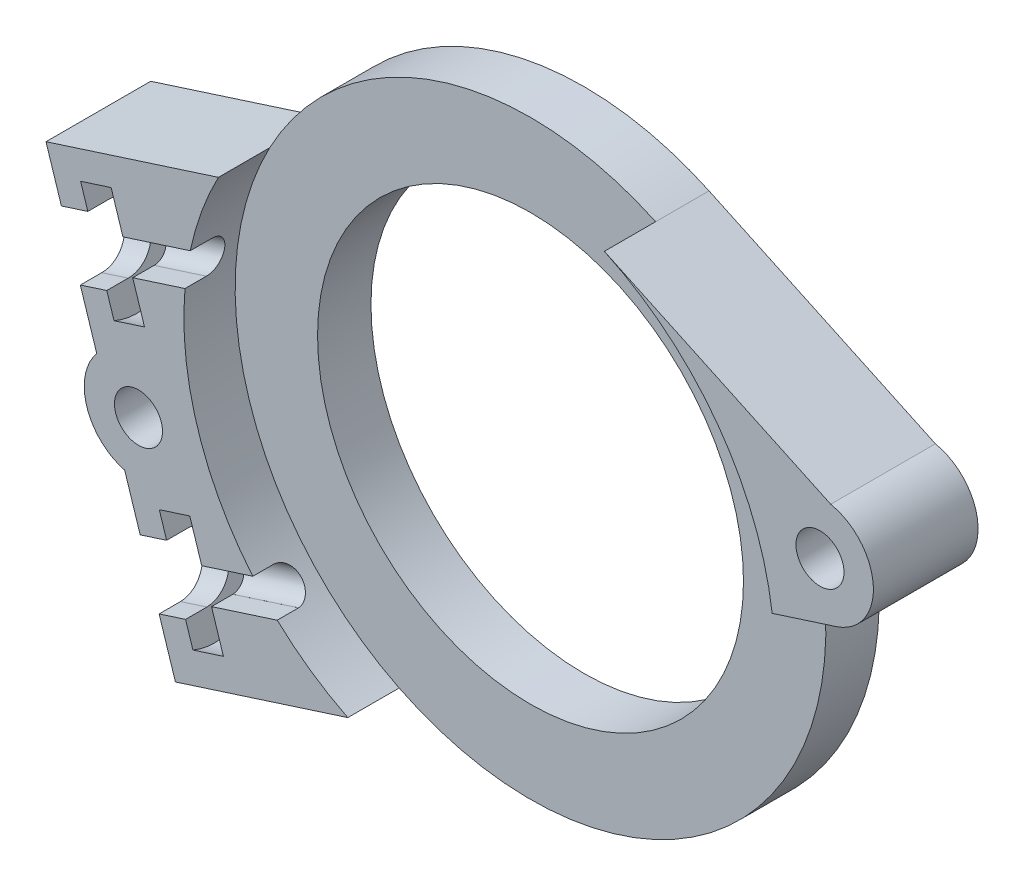
SolidWorks part; units mm, degrees
ref_plane "Alzado" through (0, 0, 0) normal (0, 0, 1) x (1, 0, 0)
ref_plane "Planta" through (0, 0, 0) normal (0, 1, 0) x (1, 0, 0)
ref_plane "Vista lateral" through (0, 0, 0) normal (1, 0, 0) x (0, 0, -1)
sketch "Croquis1" plane through (0, 0, 0) normal (0, 0, 1) x (1, 0, 0)
  circle A1 centre (0, 0) radius 27.65
extrude "Saliente-Extruir1" add sketch "Croquis1" along normal blind 5
sketch "Croquis2" plane through (0, 0, 0) normal (0, 0, -1) x (-1, 0, 0)
  line L0 (-33.4252, 5.4777) -> (-27.4211, 3.5505) construction
  line L1 (-11.7136, 25.0462) -> (-32.9036, 15.1362) construction
  line L2 (-33.4252, 5.4777) -> (-27.4211, 3.5505)
  line L3 (-11.7136, 25.0462) -> (-32.9036, 15.1362)
  line L6 (40.5555, 7.7982) -> (24.4143, 12.9793) construction
  line L7 (38.8632, 2.5261) -> (40.5555, 7.7982) construction
  line L8 (12.2993, -24.7639) -> (28.4405, -29.9449) construction
  line L9 (28.4405, -29.9449) -> (30.1924, -24.4871) construction
  line L10 (40.5555, 7.7982) -> (24.4143, 12.9793)
  line L11 (38.8632, 2.5261) -> (40.5555, 7.7982)
  line L12 (12.2993, -24.7639) -> (28.4405, -29.9449)
  line L13 (28.4405, -29.9449) -> (30.1924, -24.4871)
  line L14 (38.8632, 2.5261) -> (35.8059, -6.9986)
  line L15 (33.1901, -15.1481) -> (30.1924, -24.4871)
  line L16 (30.1924, -24.4871) -> (30.5309, -24.1624)
  arc A0 (-32.9036, 15.1362) -> (-33.4252, 5.4777) centre (-31.8971, 10.2385) ccw construction
  circle A1 centre (-31.8971, 10.2385) radius 2.25 construction
  arc A2 (-32.9036, 15.1362) -> (-33.4252, 5.4777) centre (-31.8971, 10.2385) ccw
  circle A3 centre (-31.8971, 10.2385) radius 2.25
  arc A6 (33.1901, -15.1481) -> (35.8059, -6.9986) centre (31.8971, -10.2385) ccw construction
  arc A7 (33.1901, -15.1481) -> (35.8059, -6.9986) centre (31.8971, -10.2385) ccw
  circle A8 centre (31.8971, -10.2385) radius 2.25 construction
  circle A9 centre (31.8971, -10.2385) radius 2.25
  circle A10 centre (0, 0) radius 27.65 construction
  arc A11 (-27.4211, 3.5505) -> (12.2993, -24.7639) centre (0, 0) ccw
  arc A12 (24.4143, 12.9793) -> (-11.7136, 25.0462) centre (0, 0) ccw
extrude "Saliente-Extruir2" add sketch "Croquis2" against normal up to vertex (9.8 mm away)
sketch "Croquis8" plane through (0, 0, 0) normal (0, 0, -1) x (-1, 0, 0)
  circle A0 centre (0, 0) radius 19.9363
extrude "Cortar-Extruir8" cut sketch "Croquis8" against normal through all
chamfer "Chaflán1" distance 1 angle 45 2 edges at (29.6471, 10.2385, 0) (-34.1471, -10.2385, 0)
sketch "Croquis14" plane through (-34.498, -11.0734, 0) normal (0.9522, 0.3056, 0) x (0, 0, -1)
  circle A0 centre (-7.7786, 12.2034) radius 2.9 construction
  circle A1 centre (-7.7786, 12.2034) radius 2.9
sketch "Croquis15" plane through (-32.0224, -10.2787, 0) normal (-0.9522, -0.3056, 0) x (0, 0, 1)
  circle A0 centre (7.7786, 12.2034) radius 5.5 construction
  circle A1 centre (7.7786, 12.2034) radius 5.5
sketch "Croquis16" plane through (-29.5468, -9.4841, 0) normal (0.9522, 0.3056, 0) x (0, 0, -1)
  circle A0 centre (-7.7786, 12.2034) radius 1.5 construction
  circle A1 centre (-7.7786, 12.2034) radius 1.5
sketch "Croquis18" plane through (-34.498, -11.0734, 0) normal (0.9522, 0.3056, 0) x (0, 0, -1)
  circle A0 centre (-7.8672, -11.9258) radius 2.9 construction
  circle A1 centre (-7.8672, -11.9258) radius 2.9
sketch "Croquis19" plane through (-32.0224, -10.2787, 0) normal (-0.9522, -0.3056, 0) x (0, 0, 1)
  circle A0 centre (7.8672, -11.9258) radius 5.5 construction
  circle A1 centre (7.8672, -11.9258) radius 5.5
sketch "Croquis20" plane through (-29.5468, -9.4841, 0) normal (0.9522, 0.3056, 0) x (0, 0, -1)
  circle A0 centre (-7.8672, -11.9258) radius 1.5 construction
  circle A1 centre (-7.8672, -11.9258) radius 1.5
extrude "Cortar-Extruir15" cut sketch "Croquis14" along normal blind 3
extrude "Cortar-Extruir16" cut sketch "Croquis15" against normal blind 3
extrude "Cortar-Extruir17" cut sketch "Croquis16" along normal blind 25
extrude "Cortar-Extruir18" cut sketch "Croquis18" along normal blind 3
extrude "Cortar-Extruir19" cut sketch "Croquis19" against normal blind 3
extrude "Cortar-Extruir20" cut sketch "Croquis20" along normal blind 22
sketch "Croquis21" plane through (0, 0, 9.8) normal (0, 0, 1) x (1, 0, 0)
  line L0 (-25.9795, -19.2888) -> (-25.0627, -22.1452) construction
  line L1 (-25.9795, -19.2888) -> (-25.0627, -22.1452)
  line L2 (-33.3541, 3.6859) -> (-32.4372, 0.8294) construction
  line L3 (-33.3541, 3.6859) -> (-32.4372, 0.8294)
  line L4 (-21.1973, -17.7538) -> (-25.9795, -19.2888)
  line L5 (-18.9118, -20.1709) -> (-25.0627, -22.1452)
  line L6 (-27.5457, 2.3996) -> (-32.4372, 0.8294)
  line L7 (-27.0544, 5.708) -> (-33.3541, 3.6859)
  line L8 (-39.114, 3.3074) -> (-37.3414, -2.2151) construction
  line L9 (-39.114, 3.3074) -> (-37.3414, -2.2151)
  line L10 (-31.7395, -19.6673) -> (-29.9668, -25.1898) construction
  line L11 (-31.7395, -19.6673) -> (-29.9668, -25.1898)
  line L12 (-34.8658, -1.4204) -> (-36.6384, 4.102) construction
  line L13 (-34.8658, -1.4204) -> (-36.6384, 4.102)
  line L14 (-27.4912, -24.3951) -> (-29.2639, -18.8726) construction
  line L15 (-27.4912, -24.3951) -> (-29.2639, -18.8726)
  line L16 (-39.114, 3.3074) -> (-36.6384, 4.102)
  line L17 (-37.3414, -2.2151) -> (-34.8658, -1.4204)
  line L18 (-31.7395, -19.6673) -> (-29.2639, -18.8726)
  line L19 (-27.4912, -24.3951) -> (-29.9668, -25.1898)
  arc A0 (-21.1973, -17.7538) -> (-18.9118, -20.1709) centre (0, 0) ccw construction
  arc A1 (-21.1973, -17.7538) -> (-18.9118, -20.1709) centre (0, 0) ccw
  arc A2 (-27.0544, 5.708) -> (-27.5457, 2.3996) centre (0, 0) ccw construction
  arc A3 (-27.0544, 5.708) -> (-27.5457, 2.3996) centre (0, 0) ccw
extrude "Cortar-Extruir21" cut sketch "Croquis21" against normal blind 2
